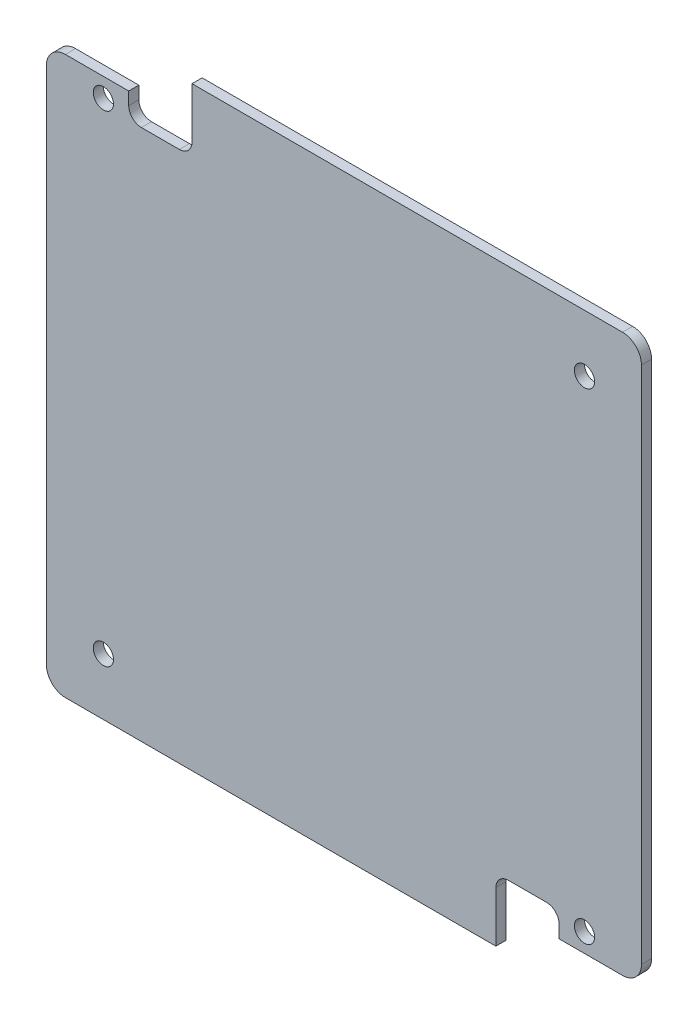
SolidWorks part; units mm, degrees
ref_plane "Front Plane" through (0, 0, 0) normal (0, 0, 1) x (1, 0, 0)
ref_plane "Top Plane" through (0, 0, 0) normal (0, 1, 0) x (1, 0, 0)
ref_plane "Right Plane" through (0, 0, 0) normal (1, 0, 0) x (0, 0, -1)
sketch "Sketch1" plane through (0, 0, 0) normal (0, 0, 1) x (1, 0, 0)
  line L1 (-84.5653, -2.0481) -> (-16.5653, -2.0481)
  line L2 (-87.5653, 0.9519) -> (-87.5653, 82.9519)
  line L3 (-64.5653, 91.9519) -> (3.4347, 91.9519)
  line L4 (6.4347, 6.9519) -> (6.4347, 88.9519)
  line L12 (3.4347, 3.9519) -> (3.4257, 3.9519)
  line L15 (-64.5653, 91.9519) -> (-64.5653, 81.9519)
  line L16 (-16.5653, 7.9519) -> (-6.5653, 7.9519)
  line L18 (-6.5653, 7.9519) -> (-6.5653, 3.9519)
  line L21 (-6.5653, 7.9519) -> (-16.5653, 7.9519)
  line L22 (-74.5653, 85.9519) -> (-84.5653, 85.9519)
  line L23 (-16.5653, 7.9519) -> (-16.5653, -2.0481)
  line L24 (3.4257, 3.9519) -> (-6.5653, 3.9519)
  line L26 (-64.5653, 81.9519) -> (-74.5653, 81.9519)
  line L28 (-74.5653, 81.9519) -> (-74.5653, 85.9519)
  arc A0 (3.4347, 3.9519) -> (6.4347, 6.9519) centre (3.4347, 6.9519) ccw
  arc A2 (-87.5653, 0.9519) -> (-84.5653, -2.0481) centre (-84.5653, 0.9519) ccw
  arc A3 (3.4347, 91.9519) -> (6.4347, 88.9519) centre (3.4347, 88.9519) cw
  arc A5 (-84.5653, 85.9519) -> (-87.5653, 82.9519) centre (-84.5653, 82.9519) ccw
  dimension "D5" = 3
  dimension "D7" = 71
  dimension "D6" = 3
  dimension "D9" = 10
  dimension "D10" = 3
  dimension "D13" = 71
  dimension "D14" = 3
  dimension "D3" = 94
  dimension "D4" = 94
  dimension "D8" = 6
  dimension "D11" = 10
  dimension "D12" = 4
  dimension "D15" = 6
  dimension "D16" = 4
extrude "Boss-Extrude1" add sketch "Sketch1" along normal blind 1.6 contours L23 L1 A2 L2 A5 L22 L28 L26 L15 L3 A3 L4 A0 L12 L24 L18 L16
hole_wizard "Ø3.2 (3.2) Diameter Hole3" positions "Sketch7" profile "Sketch6" hole size "Ø3.2" standard "Ansi Metric" end condition up to next
sketch "Sketch7" plane through (0, 0, 0) normal (0, 0, -1) x (-1, 0, 0)
  point P6 (78.5653, 6.9519)
  point P9 (78.5653, 82.9519)
  point P12 (2.5653, 82.9519)
  point P15 (2.5653, 6.9519)
sketch "Sketch6" plane through (-78.5653, 6.9519, 0) normal (1, 0, 0) x (0, 1, 0)
  line L0 (0, 0) -> (0, 1.6)
  line L1 (0, 1.6) -> (1.6, 1.6)
  line L2 (1.6, 1.6) -> (1.6, 0)
  line L5 (1.6, 0) -> (0, 0)
  line L11 (0, -6.35) -> (0, 107.95) construction
  dimension "Thru Hole Dia." = 3.2
  dimension "Thru Hole Depth" = 1.6
fillet "Fillet1" radius 2 4 edges at (-16.5653, 7.9519, 0.8) (-6.5653, 7.9519, 0.8) (-64.5653, 81.9519, 0.8) (-74.5653, 81.9519, 0.8)
